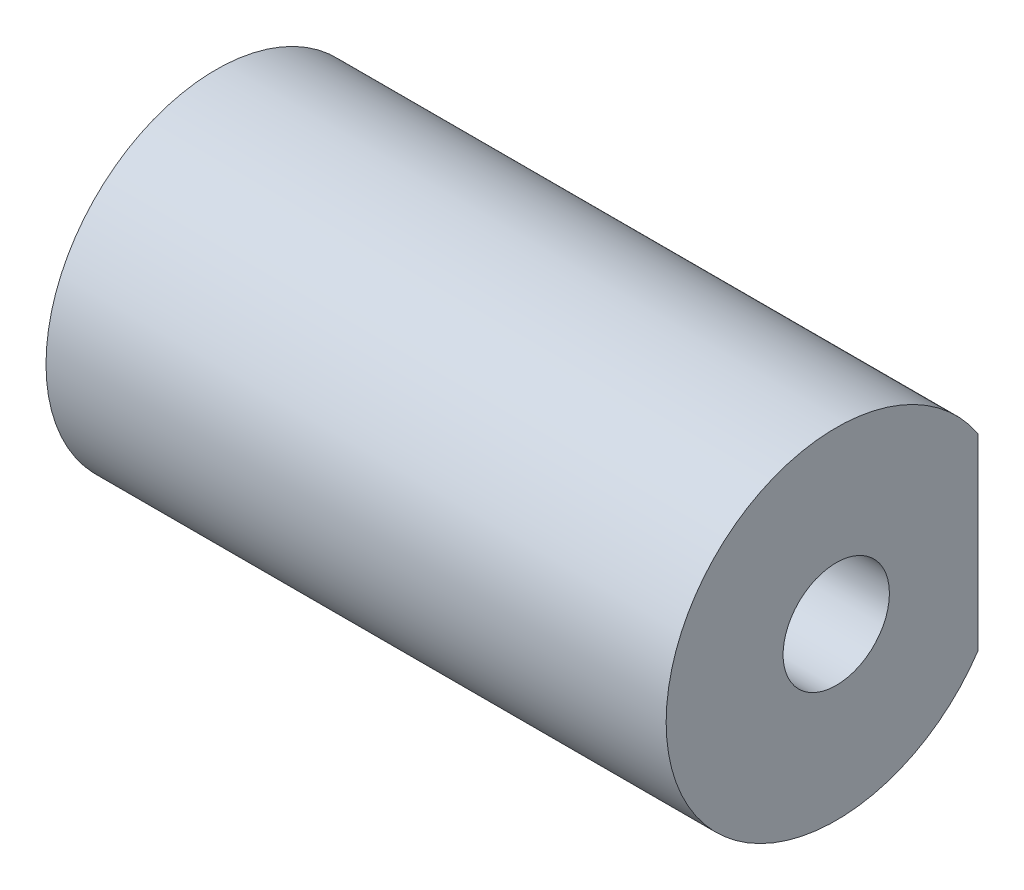
SolidWorks part; units mm, degrees
ref_plane "Front Plane" through (0, 0, 0) normal (0, 0, 1) x (1, 0, 0)
ref_plane "Top Plane" through (0, 0, 0) normal (0, 1, 0) x (1, 0, 0)
ref_plane "Right Plane" through (0, 0, 0) normal (1, 0, 0) x (0, 0, -1)
sketch "Sketch1" plane through (0, 0, 0) normal (1, 0, 0) x (0, 0, -1)
  circle A0 centre (0, 0) radius 4.8
  circle A1 centre (0, 0) radius 1.5
  dimension "D1" = 9.6
  dimension "D2" = 3
extrude "Boss-Extrude1" add sketch "Sketch1" along normal blind 17.5
sketch "Sketch2" plane through (17.5, 0, 0) normal (1, 0, 0) x (0, 0, -1)
  line L1 (4, 7.1741) -> (12.414, 7.1741)
  line L2 (4, 7.1741) -> (4, -7.3509)
  line L3 (4, -7.3509) -> (12.414, -7.3509)
  line L4 (12.414, 7.1741) -> (12.414, -7.3509)
  circle A0 centre (0, 0) radius 1.5 construction
  dimension "D1" = 4
extrude "Cut-Extrude1" cut sketch "Sketch2" against normal through all
equation "\"D1@Boss-Extrude1\"=22.5-5"
